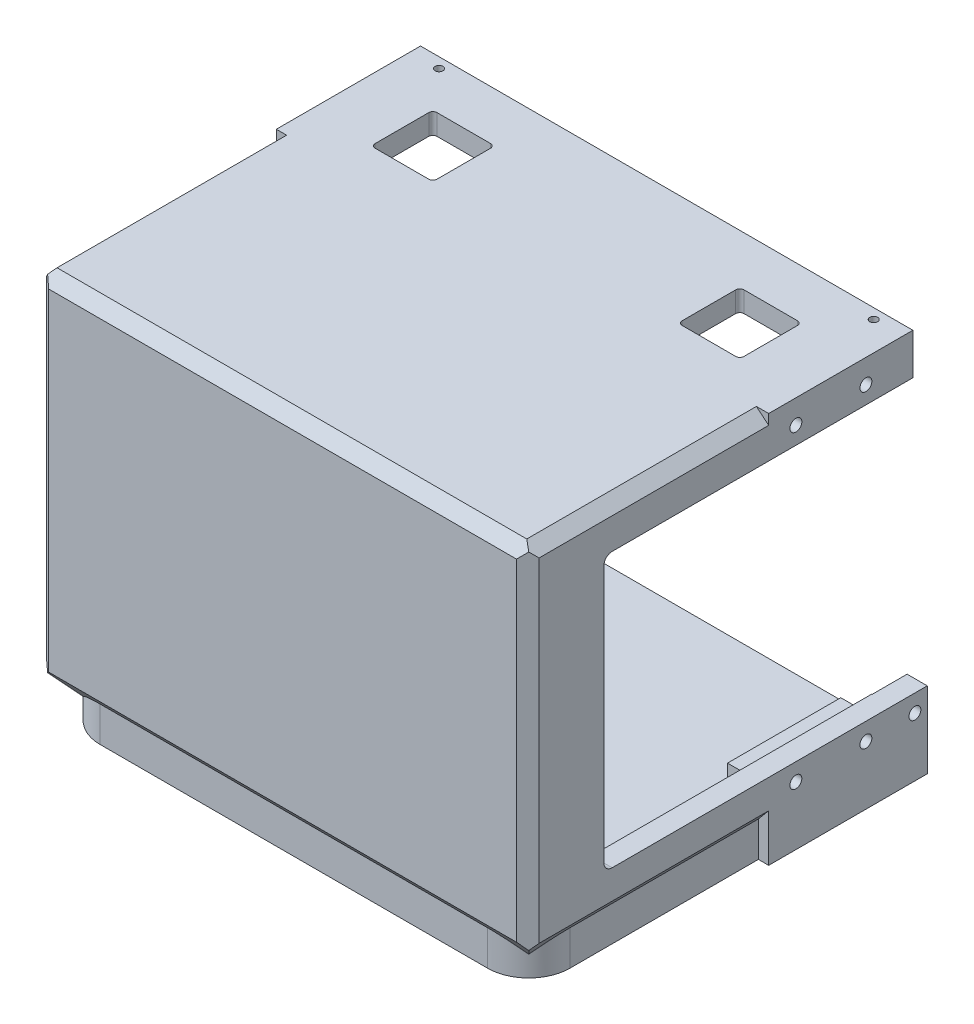
SolidWorks part; units mm, degrees
ref_plane "Front Plane" through (0, 0, 0) normal (0, 0, 1) x (1, 0, 0)
ref_plane "Top Plane" through (0, 0, 0) normal (0, 1, 0) x (1, 0, 0)
ref_plane "Right Plane" through (0, 0, 0) normal (1, 0, 0) x (0, 0, -1)
sketch "Sketch1" plane through (0, 0, 0) normal (0, 0, 1) x (1, 0, 0)
  line L1 (-59.76, -43.25) -> (59.76, -43.25)
  line L2 (-59.76, -43.25) -> (-59.76, 43.25)
  line L3 (-59.76, 43.25) -> (59.76, 43.25)
  line L4 (59.76, -43.25) -> (59.76, 43.25)
  point P4 (0, -43.25)
  point P6 (-59.76, 0)
  dimension "D1" = 86.5
  dimension "D2" = 119.52
extrude "Boss-Extrude1" add sketch "Sketch1" along normal blind 88.24
shell "Shell1" thickness 5
chamfer "Chamfer1" distance 2.5 angle 50 4 edges at (0, -43.25, 88.24) (59.76, 0, 88.24) (0, 43.25, 88.24) (-59.76, 0, 88.24)
chamfer "Chamfer2" distance 2.5 angle 50 1 edges at (-59.76, 43.25, 42.87)
chamfer "Chamfer3" distance 2.5 angle 50 3 edges at (-59.76, -43.25, 42.87) (59.76, -43.25, 42.87) (59.76, 43.25, 42.87)
sketch "Sketch3" plane through (59.76, 0, 0) normal (1, 0, 0) x (0, 0, -1)
  line L0 (0, 43.25) -> (0, 33.25)
  line L1 (0, -40.2706) -> (0, 40.75) construction
  line L2 (0, -43.25) -> (0, -33.25)
  line L4 (0, 33.25) -> (-70, 33.25)
  line L5 (0, 33.25) -> (0, -33.25)
  line L6 (0, -33.25) -> (-70, -33.25)
  line L7 (-70, 33.25) -> (-70, -33.25)
  line M6 (0, -40.2706) -> (0, 40.75)
  dimension "D1" = 10
  dimension "D2" = 10
  dimension "D3" = 70
extrude "Cut-Extrude1" cut sketch "Sketch3" against normal up to next contours L4 L7 L6 M6
fillet "Fillet1" radius 2 2 edges at (57.26, -33.25, 70) (57.26, 33.25, 70)
mirror "Mirror1" about plane through (0, 0, 0) normal (1, 0, 0) of "Cut-Extrude1", "Fillet1"
sketch "Sketch4" plane through (0, 0, 0) normal (0, 0, -1) x (-1, 0, 0)
  line L0 (-56.7806, 43.25) -> (57.26, 43.25) construction
  line L1 (-54.76, 38.25) -> (54.76, 38.25)
  line L2 (-54.76, 38.25) -> (-54.76, 43.25)
  line L3 (-54.76, 43.25) -> (54.76, 43.25)
  line L4 (54.76, 38.25) -> (54.76, 43.25)
  line L5 (54.76, 38.25) -> (54.76, -38.25) construction
  dimension "D1" = 0
extrude "Boss-Extrude2" add sketch "Sketch4" along normal blind 5
sketch "Sketch5" plane through (0, 43.25, 0) normal (0, 1, 0) x (1, 0, 0)
  line L0 (-54.76, 0) -> (54.76, 0) construction
  line L1 (-54.76, 5) -> (-54.76, 0) construction
  line L2 (54.76, 5) -> (54.76, 0) construction
  circle A0 centre (-52.76, 2.5) radius 0.95
  circle A1 centre (52.76, 2.5) radius 0.95
  point P11 (-54.76, 2.5)
  dimension "D3" = 1.9
  dimension "D4" = 1.9
  dimension "D1" = 2
  dimension "D2" = 2
extrude "Cut-Extrude2" cut sketch "Sketch5" against normal up to next
sketch "Sketch6" plane through (0, 0, 0) normal (0, 0, -1) x (-1, 0, 0)
  line L0 (-59.76, -33.25) -> (-54.86, -33.25)
  line L1 (-54.76, -33.25) -> (-59.76, -33.25) construction
  line L2 (-59.76, -33.25) -> (-59.76, -40.2706)
  line L3 (-59.76, -40.2706) -> (-57.26, -43.25)
  line L4 (-54.86, -33.25) -> (-54.86, -43.25)
  line L5 (56.7806, -43.25) -> (-57.26, -43.25) construction
  line L6 (-54.86, -43.25) -> (-57.26, -43.25)
  dimension "D1" = 4.9
extrude "Boss-Extrude3" add sketch "Sketch6" along normal blind 8.5
sketch "Sketch8" plane through (0, 0, 0) normal (0, 0, -1) x (-1, 0, 0)
  line L0 (57.26, 43.25) -> (54.76, 43.25) construction
  line L1 (54.76, 43.25) -> (54.76, 38.25) construction
  line L2 (54.76, 38.25) -> (54.76, 33.25) construction
  line L3 (54.76, 33.25) -> (59.76, 33.25) construction
  line L4 (59.76, 33.25) -> (59.76, 40.2706) construction
  line L5 (59.76, 40.2706) -> (57.26, 43.25) construction
  line L6 (-54.76, 33.25) -> (-54.76, 38.25) construction
  line L7 (-54.76, 38.25) -> (-54.76, 43.25) construction
  line L8 (-54.76, 43.25) -> (-56.7806, 43.25) construction
  line L9 (-56.7806, 43.25) -> (-59.76, 40.75) construction
  line L10 (-59.76, 40.75) -> (-59.76, 33.25) construction
  line L11 (-59.76, 33.25) -> (-54.76, 33.25) construction
  line L12 (57.26, 43.25) -> (54.76, 43.25)
  line L13 (54.76, 43.25) -> (54.76, 38.25)
  line L14 (54.76, 38.25) -> (54.76, 33.25)
  line L15 (54.76, 33.25) -> (59.76, 33.25)
  line L16 (59.76, 33.25) -> (59.76, 40.2706)
  line L17 (59.76, 40.2706) -> (57.26, 43.25)
  line L18 (-54.76, 33.25) -> (-54.76, 38.25)
  line L19 (-54.76, 38.25) -> (-54.76, 43.25)
  line L20 (-54.76, 43.25) -> (-56.7806, 43.25)
  line L21 (-56.7806, 43.25) -> (-59.76, 40.75)
  line L22 (-59.76, 40.75) -> (-59.76, 33.25)
  line L23 (-59.76, 33.25) -> (-54.76, 33.25)
extrude "Boss-Extrude4" add sketch "Sketch8" along normal blind 5
sketch "Sketch10" plane through (0, 0, -5) normal (0, 0, -1) x (-1, 0, 0)
  line L0 (-59.76, 40.75) -> (-59.76, 43.25)
  line L1 (-56.7806, 43.25) -> (-59.76, 43.25)
  line L2 (-59.76, 40.75) -> (-56.7806, 43.25)
extrude "Boss-Extrude6" add sketch "Sketch10" against normal blind 35
sketch "Sketch11" plane through (0, 0, 0) normal (0, 0, -1) x (-1, 0, 0)
  line L0 (59.76, -33.25) -> (54.86, -33.25)
  line L1 (59.76, -33.25) -> (54.76, -33.25) construction
  line L2 (54.86, -33.25) -> (54.86, -43.25)
  line L3 (56.7806, -43.25) -> (-54.86, -43.25) construction
  line L4 (54.86, -43.25) -> (56.7806, -43.25)
  line L5 (56.7806, -43.25) -> (59.76, -40.75)
  line L6 (59.76, -40.75) -> (59.76, -33.25)
  dimension "D1" = 4.9
extrude "Boss-Extrude7" add sketch "Sketch11" along normal blind 8.5
sketch "Sketch13" plane through (0, 0, -5) normal (0, 0, -1) x (-1, 0, 0)
  line L0 (57.26, 43.25) -> (59.76, 43.25)
  line L1 (59.76, 40.2706) -> (59.76, 43.25)
  line L2 (57.26, 43.25) -> (59.76, 40.2706)
extrude "Boss-Extrude8" add sketch "Sketch13" against normal blind 35
sketch "Sketch14" plane through (0, 0, -8.5) normal (0, 0, -1) x (-1, 0, 0)
  line L0 (-59.76, -40.2706) -> (-59.76, -43.25)
  line L1 (-57.26, -43.25) -> (-59.76, -43.25)
  line L2 (59.76, -40.75) -> (59.76, -43.25)
  line L3 (56.7806, -43.25) -> (59.76, -43.25)
  line L4 (56.7806, -43.25) -> (59.76, -40.75)
  line L5 (-59.76, -40.2706) -> (-57.26, -43.25)
extrude "Boss-Extrude9" add sketch "Sketch14" against normal blind 38.5
sketch "Sketch15" plane through (59.76, 0, 0) normal (1, 0, 0) x (0, 0, -1)
  line L0 (5, 37.5) -> (-6.4, 37.5) construction
  line L1 (5, 43.25) -> (5, 33.25) construction
  line L2 (-30, 43.25) -> (5, 43.25) construction
  line L3 (-6.4, 37.5) -> (-23.4, 37.5) construction
  line L4 (-6.4, 36.05) -> (-6.4, 33.25) construction
  line L5 (5, 33.25) -> (-68, 33.25) construction
  circle A0 centre (-6.4, 37.5) radius 1.45
  circle A1 centre (-23.4, 37.5) radius 1.45
  dimension "D4" = 2.9
  dimension "D5" = 2.9
  dimension "D1" = 5.75
  dimension "D2" = 11.4
  dimension "D3" = 17
sketch "Sketch16" plane through (0, 38.25, 0) normal (0, -1, 0) x (1, 0, 0)
  line L0 (54.76, 2.5) -> (49.76, 2.5)
  line L1 (54.76, -5) -> (54.76, 68) construction
  line L2 (49.76, 2.5) -> (49.76, 30)
  line L3 (49.76, 30) -> (54.76, 30)
  line L4 (54.76, 83.24) -> (54.76, -5) construction
  line L5 (54.76, -5) -> (-54.76, -5) construction
  line L6 (54.76, 30) -> (54.76, 2.5)
  dimension "D1" = 35
  dimension "D2" = 7.5
  dimension "D3" = 5
extrude "Boss-Extrude10" add sketch "Sketch16" along normal blind 3
mirror "Mirror6" about plane through (0, 0, 0) normal (1, 0, 0) of "Boss-Extrude10"
mirror "Mirror7" about plane through (0, 0, 0) normal (0, 1, 0) of "Mirror6", "Boss-Extrude10"
extrude "Cut-Extrude5" cut sketch "Sketch15" against normal blind 8
mirror "Mirror8" about plane through (0, 0, 0) normal (0, 1, 0) of "Cut-Extrude5" second plane through (0, 0, 0) second plane normal (1, 0, 0)
sketch "Sketch17" plane through (59.76, 0, 0) normal (1, 0, 0) x (0, 0, -1)
  line L0 (-6.4, -37.5) -> (8.5, -37.5) construction
  line L1 (8.5, -33.25) -> (8.5, -43.25) construction
  line L2 (5.5, -37.5) -> (5.5, -43.25) construction
  line L3 (-30, -43.25) -> (8.5, -43.25) construction
  circle A0 centre (5.5, -37.5) radius 1.45
  dimension "D1" = 2.9
extrude "Cut-Extrude6" cut sketch "Sketch17" against normal blind 8
sketch "Sketch18" plane through (-54.86, 0, 0) normal (1, 0, 0) x (0, 0, -1)
  circle A0 centre (5.5, -37.5) radius 1.45 construction
  circle A1 centre (5.5, -37.5) radius 1.45
extrude "Cut-Extrude7" cut sketch "Sketch18" against normal blind 8
sketch "Sketch19" plane through (0, 43.25, 0) normal (0, 1, 0) x (1, 0, 0)
  line L0 (-59.76, -30) -> (-59.76, 5) construction
  line L1 (-44.76, -22) -> (-29.76, -22)
  line L2 (-44.76, -22) -> (-44.76, -7)
  line L3 (-44.76, -7) -> (-29.76, -7)
  line L4 (-29.76, -22) -> (-29.76, -7)
  line L5 (-59.76, 5) -> (59.76, 5) construction
  dimension "D1" = 15
  dimension "D2" = 15
  dimension "D3" = 15
  dimension "D4" = 12
extrude "Cut-Extrude8" cut sketch "Sketch19" against normal blind 5
fillet "Fillet2" radius 1 4 edges at (-29.76, 40.75, 7) (-44.76, 40.75, 7) (-29.76, 40.75, 22) (-44.76, 40.75, 22)
mirror "Mirror10" about plane through (0, 0, 0) normal (1, 0, 0) of "Cut-Extrude8", "Fillet2"
sketch "Sketch20" plane through (0, -43.25, 0) normal (0, -1, 0) x (1, 0, 0)
  line L0 (59.76, 30) -> (59.76, -8.5) construction
  line L1 (-56.7806, 85.74) -> (57.26, 85.74)
  line L2 (-56.7806, 85.74) -> (-56.7806, 30)
  line L4 (57.26, 85.74) -> (57.26, 30)
  line L5 (-59.76, 30) -> (-56.7806, 30)
  line L6 (-59.76, 30) -> (-59.76, 0)
  line L7 (-54.86, 0) -> (54.86, 0)
  line L8 (59.76, 30) -> (59.76, 0)
  line L9 (57.26, 30) -> (59.76, 30)
  line L11 (59.76, 0) -> (59.76, -8.5)
  line L12 (59.76, -8.5) -> (54.86, -8.5)
  line L13 (54.86, 0) -> (54.86, -8.5)
  line L15 (-59.76, 0) -> (-59.76, -8.5)
  line L16 (-59.76, -8.5) -> (-54.86, -8.5)
  line L17 (-54.86, 0) -> (-54.86, -8.5)
extrude "Boss-Extrude11" add sketch "Sketch20" along normal blind 8.5
fillet "Fillet3" radius 10 2 edges at (-56.7806, -47.5, 85.74) (57.26, -47.5, 85.74)
